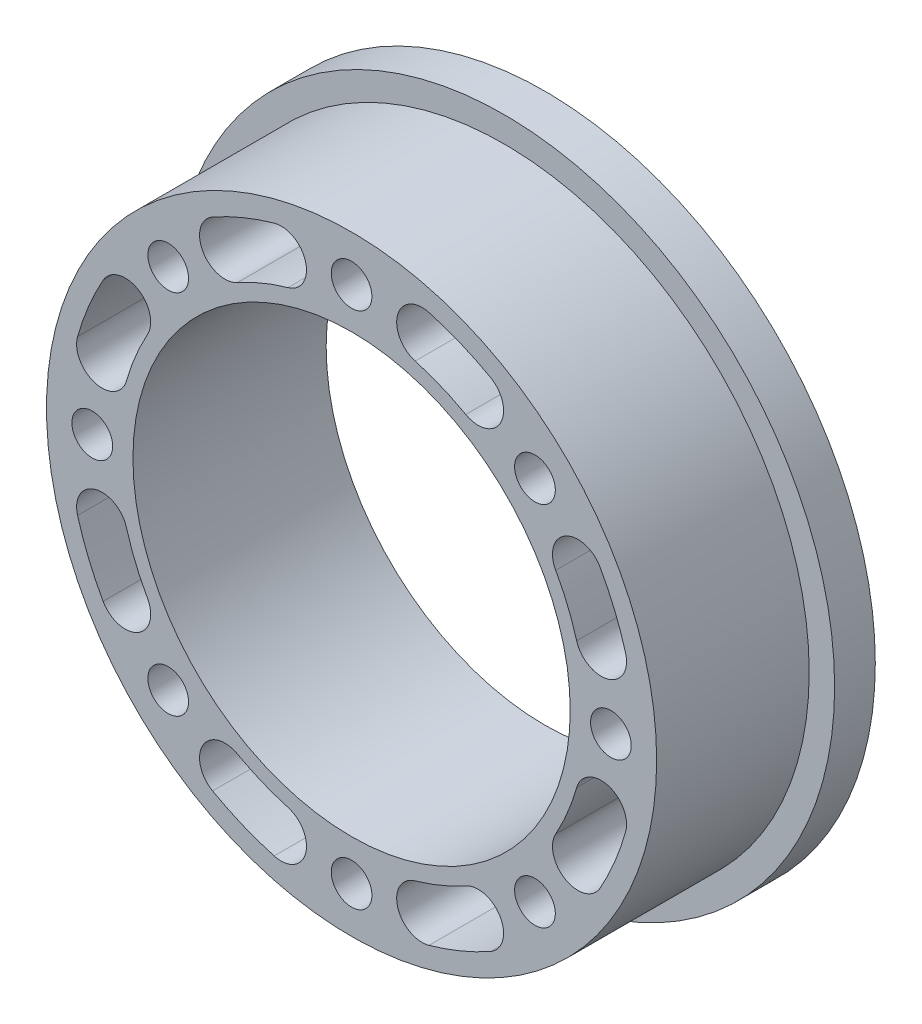
SolidWorks part; units mm, degrees
material "6061 合金"
ref_plane "前视基准面" through (0, 0, 0) normal (0, 0, 1) x (1, 0, 0)
ref_plane "上视基准面" through (0, 0, 0) normal (0, 1, 0) x (1, 0, 0)
ref_plane "右视基准面" through (0, 0, 0) normal (1, 0, 0) x (0, 0, -1)
other "Configuration Table"
sketch "草图1" plane through (0, 0, 0) normal (0, 0, 1) x (1, 0, 0)
  line L0 (0, 0) -> (0, 25.5) construction
  circle A0 centre (0, 0) radius 32.5
  circle A1 centre (0, 0) radius 21.5
  circle A2 centre (0, 0) radius 25.5 construction
  circle A3 centre (0, 25.5) radius 2 construction
  circle A4 centre (18.0312, 18.0312) radius 2 construction
  circle A5 centre (25.5, 0) radius 2 construction
  circle A6 centre (18.0312, -18.0312) radius 2 construction
  circle A7 centre (0, -25.5) radius 2 construction
  circle A8 centre (-18.0312, -18.0312) radius 2 construction
  circle A9 centre (-25.5, 0) radius 2 construction
  circle A10 centre (-18.0312, 18.0312) radius 2 construction
  dimension "D1" = 65
  dimension "D2" = 4
  dimension "D3" = 51
  dimension "D4" = 4
  dimension "D5" = 8
extrude "凸台-拉伸1" add sketch "草图1" along normal blind 4
sketch "草图2" plane through (0, 0, 4) normal (0, 0, 1) x (1, 0, 0)
  circle A0 centre (0, 0) radius 30
  circle A1 centre (0, 0) radius 21.5
  circle A2 centre (0, 0) radius 21.5 construction
  dimension "D1" = 60
extrude "凸台-拉伸2" add sketch "草图2" along normal blind 15
sketch "草图3" plane through (0, 0, 0) normal (0, 0, -1) x (-1, 0, 0)
  line L0 (0, 0) -> (15.0251, 36.2738) construction
  circle A0 centre (18.0312, 18.0312) radius 2 construction
  circle A1 centre (25.5, 0) radius 2 construction
  circle A2 centre (18.0312, -18.0312) radius 2 construction
  circle A3 centre (0, -25.5) radius 2 construction
  circle A4 centre (-18.0312, -18.0312) radius 2 construction
  circle A5 centre (-25.5, 0) radius 2 construction
  circle A6 centre (-18.0312, 18.0312) radius 2 construction
  circle A7 centre (0, 25.5) radius 2 construction
  circle A8 centre (18.0312, 18.0312) radius 2
  circle A9 centre (25.5, 0) radius 2
  circle A10 centre (18.0312, -18.0312) radius 2
  circle A11 centre (0, -25.5) radius 2
  circle A12 centre (-18.0312, -18.0312) radius 2
  circle A13 centre (-25.5, 0) radius 2
  circle A14 centre (-18.0312, 18.0312) radius 2
  circle A15 centre (0, 25.5) radius 2
  circle A16 centre (0, 0) radius 25.5 construction
  arc A17 (7.6135, 26.945) -> (13.6694, 24.4366) centre (0, 0) cw
  arc A18 (6.254, 22.1334) -> (11.2285, 20.0729) centre (0, 0) cw
  arc A19 (13.6694, 24.4366) -> (11.2285, 20.0729) centre (12.4489, 22.2547) cw
  arc A20 (7.6135, 26.945) -> (6.254, 22.1334) centre (6.9338, 24.5392) ccw
  arc A22 (24.4366, 13.6694) -> (20.0729, 11.2285) centre (22.2547, 12.4489) ccw
  arc A23 (20.0729, 11.2285) -> (22.1334, 6.254) centre (0, 0) cw
  arc A24 (26.945, 7.6135) -> (22.1334, 6.254) centre (24.5392, 6.9338) cw
  arc A25 (24.4366, 13.6694) -> (26.945, 7.6135) centre (0, 0) cw
  arc A26 (26.945, -7.6135) -> (22.1334, -6.254) centre (24.5392, -6.9338) ccw
  arc A27 (22.1334, -6.254) -> (20.0729, -11.2285) centre (0, 0) cw
  arc A28 (24.4366, -13.6694) -> (20.0729, -11.2285) centre (22.2547, -12.4489) cw
  arc A29 (26.945, -7.6135) -> (24.4366, -13.6694) centre (0, 0) cw
  arc A30 (13.6694, -24.4366) -> (11.2285, -20.0729) centre (12.4489, -22.2547) ccw
  arc A31 (11.2285, -20.0729) -> (6.254, -22.1334) centre (0, 0) cw
  arc A32 (7.6135, -26.945) -> (6.254, -22.1334) centre (6.9338, -24.5392) cw
  arc A33 (13.6694, -24.4366) -> (7.6135, -26.945) centre (0, 0) cw
  arc A34 (-7.6135, -26.945) -> (-6.254, -22.1334) centre (-6.9338, -24.5392) ccw
  arc A35 (-6.254, -22.1334) -> (-11.2285, -20.0729) centre (0, 0) cw
  arc A36 (-13.6694, -24.4366) -> (-11.2285, -20.0729) centre (-12.4489, -22.2547) cw
  arc A37 (-7.6135, -26.945) -> (-13.6694, -24.4366) centre (0, 0) cw
  arc A38 (-24.4366, -13.6694) -> (-20.0729, -11.2285) centre (-22.2547, -12.4489) ccw
  arc A39 (-20.0729, -11.2285) -> (-22.1334, -6.254) centre (0, 0) cw
  arc A40 (-26.945, -7.6135) -> (-22.1334, -6.254) centre (-24.5392, -6.9338) cw
  arc A41 (-24.4366, -13.6694) -> (-26.945, -7.6135) centre (0, 0) cw
  arc A42 (-26.945, 7.6135) -> (-22.1334, 6.254) centre (-24.5392, 6.9338) ccw
  arc A43 (-22.1334, 6.254) -> (-20.0729, 11.2285) centre (0, 0) cw
  arc A44 (-24.4366, 13.6694) -> (-20.0729, 11.2285) centre (-22.2547, 12.4489) cw
  arc A45 (-26.945, 7.6135) -> (-24.4366, 13.6694) centre (0, 0) cw
  arc A46 (-13.6694, 24.4366) -> (-11.2285, 20.0729) centre (-12.4489, 22.2547) ccw
  arc A47 (-11.2285, 20.0729) -> (-6.254, 22.1334) centre (0, 0) cw
  arc A48 (-7.6135, 26.945) -> (-6.254, 22.1334) centre (-6.9338, 24.5392) cw
  arc A49 (-13.6694, 24.4366) -> (-7.6135, 26.945) centre (0, 0) cw
  dimension "D1" = 5
  dimension "D2" = 7
  dimension "D3" = 8
extrude "切除-拉伸1" cut sketch "草图3" against normal through all
